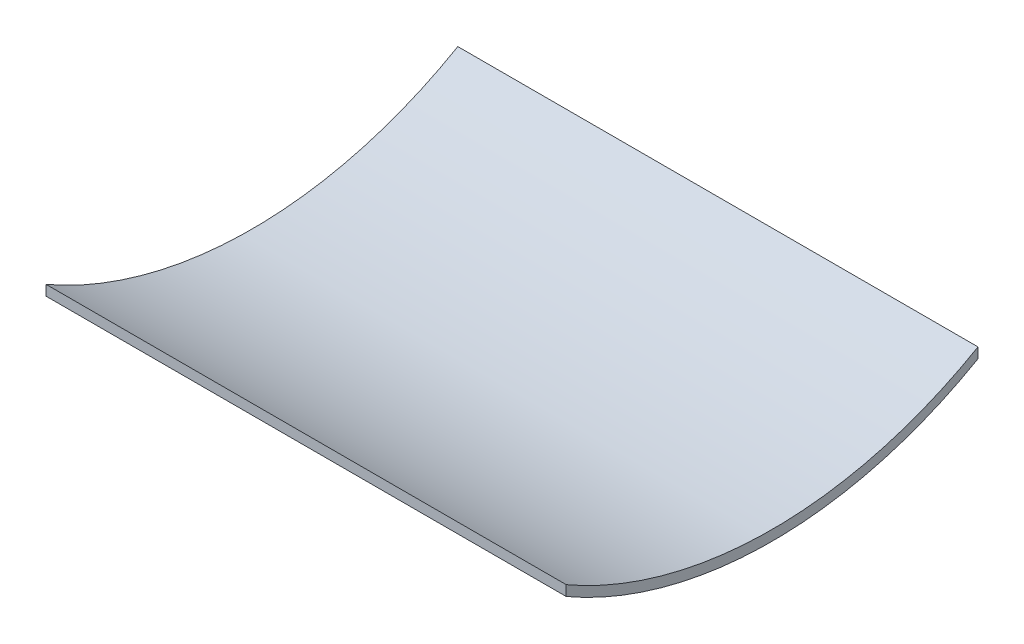
SolidWorks part; units mm, degrees
ref_plane "Front Plane" through (0, 0, 0) normal (0, 0, 1) x (1, 0, 0)
ref_plane "Top Plane" through (0, 0, 0) normal (0, 1, 0) x (1, 0, 0)
ref_plane "Right Plane" through (0, 0, 0) normal (1, 0, 0) x (0, 0, -1)
sketch "Sketch3" plane through (0, 0, 0) normal (1, 0, 0) x (0, 0, -1)
  line L0 (-8.3933, 1.9614) -> (-8.3933, -4.052)
  line L6 (-8.3933, -4.3886) -> (-8.3933, 1.9614)
  line L8 (232.9067, -4.3886) -> (232.9067, 1.9614)
  line L9 (232.9067, -4.052) -> (232.9067, 1.9614)
  arc A2 (-8.3933, 1.9614) -> (232.9067, 1.9614) centre (112.2567, 210.9333) ccw
  arc A3 (-8.3933, -4.052) -> (232.9067, -4.052) centre (112.2567, 204.9199) ccw
  dimension "D1" = 6.35
  dimension "D2" = 241.3
extrude "Boss-Extrude4" add sketch "Sketch3" along normal blind 304.8 contours L0 A3 L8 A2
ref_plane "Plane1" through (0, 1.9614, 0) normal (0, 1, 0) x (1, 0, 0)
